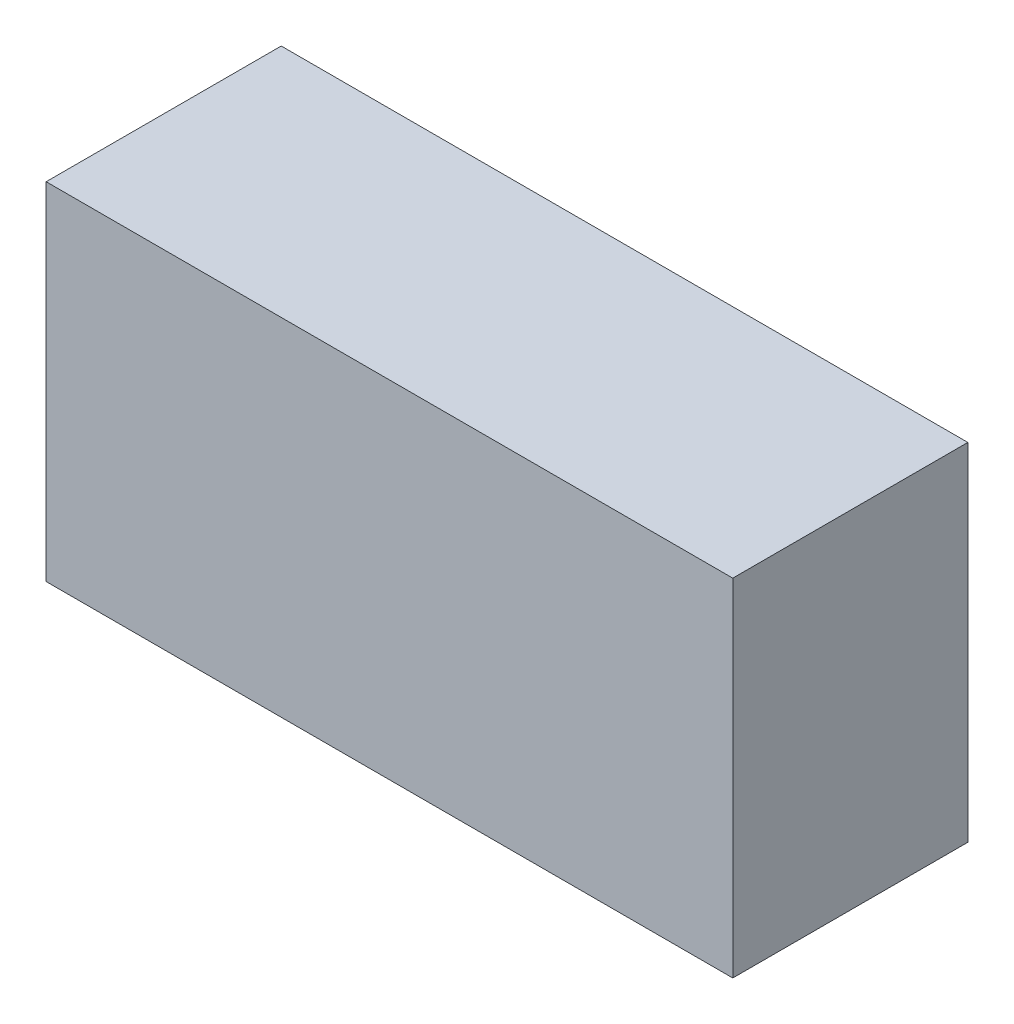
SolidWorks part; units mm, degrees
ref_plane "Front Plane" through (0, 0, 0) normal (0, 0, 1) x (1, 0, 0)
ref_plane "Top Plane" through (0, 0, 0) normal (0, 1, 0) x (1, 0, 0)
ref_plane "Right Plane" through (0, 0, 0) normal (1, 0, 0) x (0, 0, -1)
sketch "Sketch1" plane through (0, 0, 0) normal (0, 0, 1) x (1, 0, 0)
  line L0 (-1.4224, 0.7366) -> (1.4986, 0.7366)
  line L1 (1.4986, 0.7366) -> (1.4986, -0.7366)
  line L2 (1.4986, -0.7366) -> (-1.4224, -0.7366)
  line L3 (-1.4224, -0.7366) -> (-1.4224, 0.7366)
extrude "Component_Outline" add sketch "Sketch1" along normal blind 1 separate body
sketch3d "3DSketch1"
  line L0 (0, 0, 0) -> (1, 0, 0)
  line L1 (0, 0, 0) -> (0, 1, 0)
  line L2 (0, 0, 0) -> (0, 0, 1)
  point P0 (0, 0, 0)
